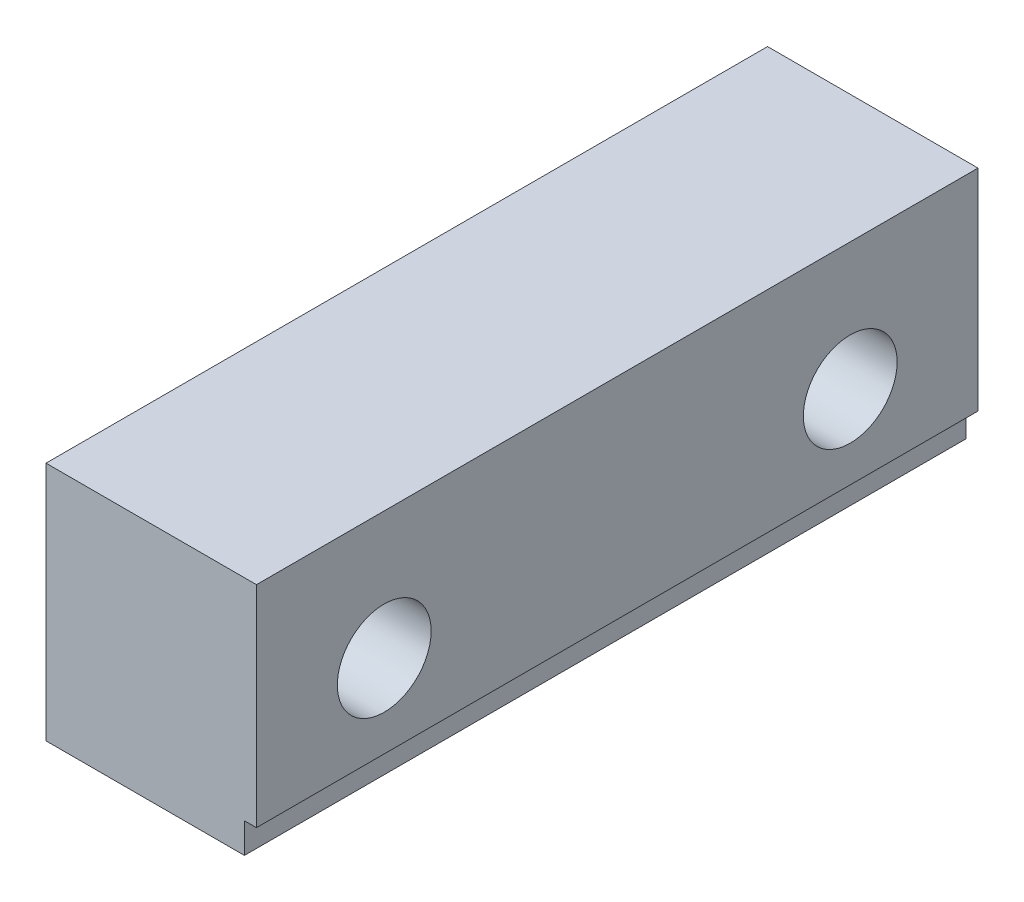
SolidWorks part; units mm, degrees
ref_plane "Front Plane" through (0, 0, 0) normal (0, 0, 1) x (1, 0, 0)
ref_plane "Top Plane" through (0, 0, 0) normal (0, 1, 0) x (1, 0, 0)
ref_plane "Right Plane" through (0, 0, 0) normal (1, 0, 0) x (0, 0, -1)
sketch "Sketch1" plane through (0, 0, 0) normal (0, 0, 1) x (1, 0, 0)
  line L1 (22.225, -25.4) -> (-22.225, -25.4)
  line L2 (22.225, -25.4) -> (22.225, 25.4)
  line L3 (22.225, 25.4) -> (-22.225, 25.4)
  line L4 (-22.225, -25.4) -> (-22.225, 25.4)
  line L5 (22.225, -25.4) -> (-22.225, 25.4) construction
  line L6 (22.225, 25.4) -> (-22.225, -25.4) construction
  point P0 (0, 0)
  dimension "D1" = 44.45
  dimension "D2" = 50.8
extrude "Boss-Extrude1" add sketch "Sketch1" along normal mid plane 152.4
sketch "Sketch2" plane through (22.225, 0, 0) normal (1, 0, 0) x (0, 0, -1)
  line L0 (-76.2, -25.4) -> (76.2, -25.4) construction
  circle A0 centre (-49.2125, -1.524) radius 6.731
  circle A1 centre (49.2125, -1.524) radius 6.731
  dimension "D4" = 13.462
  dimension "D1" = 98.425
  dimension "D2" = 49.2125
  dimension "D3" = 23.876
extrude "Cut-Extrude1" cut sketch "Sketch2" against normal up to next
sketch "Sketch3" plane through (22.225, 0, 0) normal (1, 0, 0) x (0, 0, -1)
  circle A0 centre (-49.2125, -1.524) radius 9.906
  circle A1 centre (49.2125, -1.524) radius 9.906
  dimension "D1" = 19.812
extrude "Cut-Extrude2" cut sketch "Sketch3" against normal blind 38.608
sketch "Sketch4" plane through (0, 0, 76.2) normal (0, 0, 1) x (1, 0, 0)
  line L7 (22.225, -25.4) -> (19.685, -25.4)
  line L8 (22.225, -25.4) -> (22.225, -19.05)
  line L9 (22.225, -19.05) -> (19.685, -19.05)
  line L10 (19.685, -25.4) -> (19.685, -19.05)
  dimension "D1" = 2.54
  dimension "D2" = 6.35
extrude "Cut-Extrude4" cut sketch "Sketch4" against normal through all
